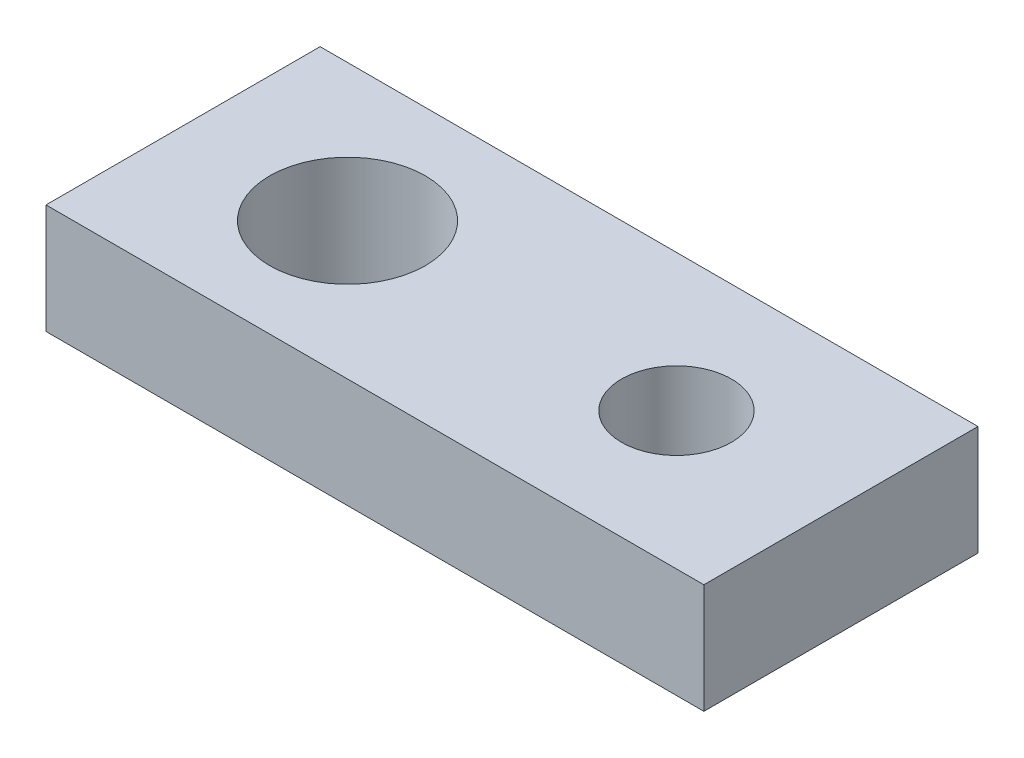
SolidWorks part; units mm, degrees
ref_plane "Front Plane" through (0, 0, 0) normal (0, 0, 1) x (1, 0, 0)
ref_plane "Top Plane" through (0, 0, 0) normal (0, 1, 0) x (1, 0, 0)
ref_plane "Right Plane" through (0, 0, 0) normal (1, 0, 0) x (0, 0, -1)
sketch "Sketch1" plane through (0, 0, 0) normal (0, 1, 0) x (1, 0, 0)
  line L1 (-38.1, -15.875) -> (38.1, -15.875)
  line L2 (-38.1, -15.875) -> (-38.1, 15.875)
  line L3 (-38.1, 15.875) -> (38.1, 15.875)
  line L4 (38.1, -15.875) -> (38.1, 15.875)
  line L5 (-38.1, -15.875) -> (38.1, 15.875) construction
  line L6 (-38.1, 15.875) -> (38.1, -15.875) construction
  point P0 (0, 0)
  dimension "D1" = 76.2
  dimension "D2" = 31.75
extrude "Boss-Extrude1" add sketch "Sketch1" along normal blind 12.7
sketch "Sketch2" plane through (0, 12.7, 0) normal (0, 1, 0) x (1, 0, 0)
  line L0 (0, 0) -> (-38.1, 0) construction
  line L1 (-38.1, 15.875) -> (-38.1, -15.875) construction
  line L2 (0, 0) -> (38.1, 0) construction
  line L3 (38.1, -15.875) -> (38.1, 15.875) construction
  circle A0 centre (-19.05, 0) radius 9.017
  circle A1 centre (19.05, 0) radius 6.3627
  point P4 (0, 0)
  point P13 (0, 0)
  dimension "D1" = 18.034
  dimension "D2" = 12.7254
extrude "Cut-Extrude1" cut sketch "Sketch2" against normal through all
